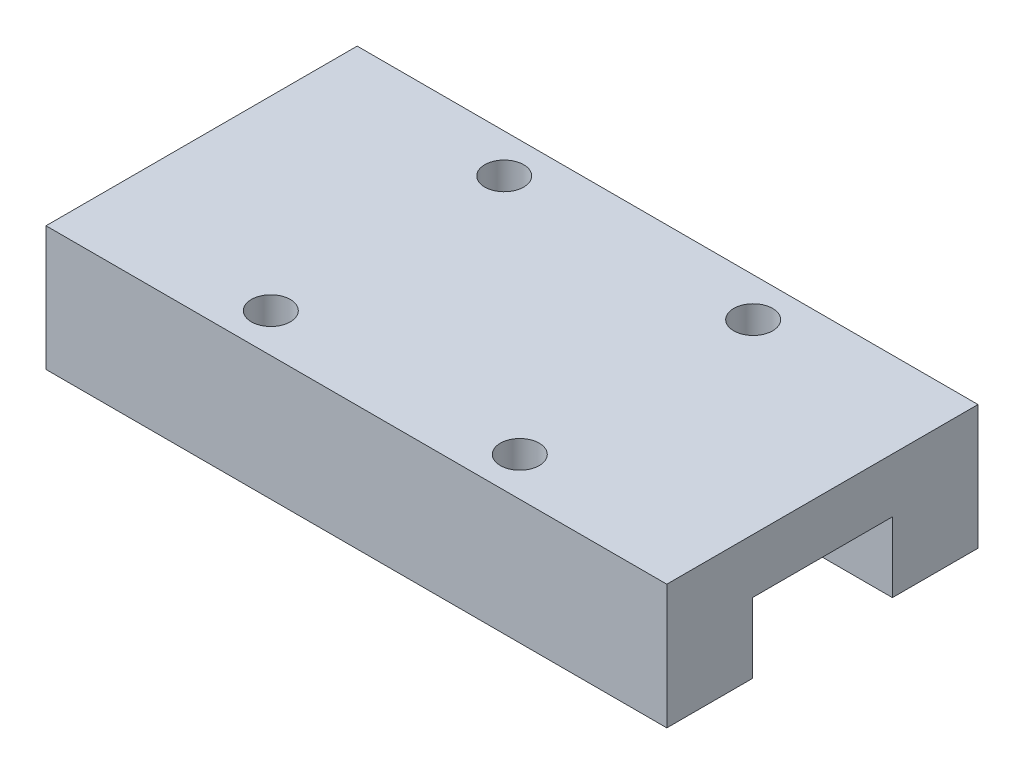
SolidWorks part; units mm, degrees
material "1023 碳钢板 (SS)"
ref_plane "前视基准面" through (0, 0, 0) normal (0, 0, 1) x (1, 0, 0)
ref_plane "上视基准面" through (0, 0, 0) normal (0, 1, 0) x (1, 0, 0)
ref_plane "右视基准面" through (0, 0, 0) normal (1, 0, 0) x (0, 0, -1)
sketch "草图1" plane through (0, 0, 0) normal (1, 0, 0) x (0, 0, -1)
  line L0 (0, 0) -> (0, 8)
  line L1 (0, 8) -> (20, 8)
  line L2 (20, 8) -> (20, 0)
  line L3 (20, 0) -> (14.5, 0)
  line L4 (14.5, 0) -> (14.5, 4.5)
  line L5 (14.5, 4.5) -> (5.5, 4.5)
  line L6 (5.5, 4.5) -> (5.5, 0)
  line L7 (5.5, 0) -> (0, 0)
  line L8 (10, 8) -> (10, -30.3326) construction
  dimension "D1" = 20
  dimension "D2" = 8
  dimension "D3" = 9
  dimension "D4" = 3.5
extrude "凸台-拉伸1" add sketch "草图1" along normal mid plane 39.9
sketch "草图2" plane through (0, 8, 0) normal (0, 1, 0) x (1, 0, 0)
  line L0 (-19.95, 10) -> (19.95, 10) construction
  line L1 (-19.95, 20) -> (-19.95, 0) construction
  line L2 (19.95, 20) -> (19.95, 0) construction
  line L3 (0, 17.5) -> (19.95, 17.5) construction
  line L4 (0, 2.5) -> (19.95, 2.5) construction
  line L5 (0, 20) -> (0, 0) construction
  line L6 (19.95, 20) -> (-19.95, 20) construction
  line L7 (19.95, 0) -> (-19.95, 0) construction
  circle A0 centre (-8, 17.5) radius 1.3919
  circle A1 centre (-8, 2.5) radius 1.3919
  circle A2 centre (8, 2.5) radius 1.3919
  circle A3 centre (8, 17.5) radius 1.3919
  dimension "D2" = 16
  dimension "D3" = 2.7838
  dimension "D1" = 7.5
hole_wizard "M3 螺纹孔1" positions "草图3" profile "草图4" tap size "M3" standard "GB"
sketch "草图3" plane through (0, 8, 0) normal (0, 1, 0) x (1, 0, 0)
  point P0 (-8, 17.5)
  point P3 (8, 17.5)
  point P6 (8, 2.5)
  point P9 (-8, 2.5)
cosmetic thread "孔螺蚊线1" parameters "D1"=3, "D2"=3
cosmetic thread "孔螺蚊线2" parameters "D1"=3, "D2"=3
cosmetic thread "孔螺蚊线3" parameters "D1"=3, "D2"=3
cosmetic thread "孔螺蚊线4" parameters "D1"=3, "D2"=3
sketch "草图4" plane through (-8, 8, -17.5) normal (1, 0, 0) x (0, 0, 1)
  line L0 (0, 0) -> (0, 5.2511)
  line L1 (0, 5.2511) -> (1.25, 4.5)
  line L2 (1.25, 4.5) -> (1.25, 0)
  line L5 (1.25, 0) -> (0, 0)
  line L10 (0, 5.2511) -> (-1.25, 4.5) construction
  line L11 (0, -6.35) -> (0, 107.95) construction
  dimension "螺纹孔钻头直径" = 2.5
  dimension "螺纹孔钻头深度" = 4.5
  dimension "导头角度" = 118
